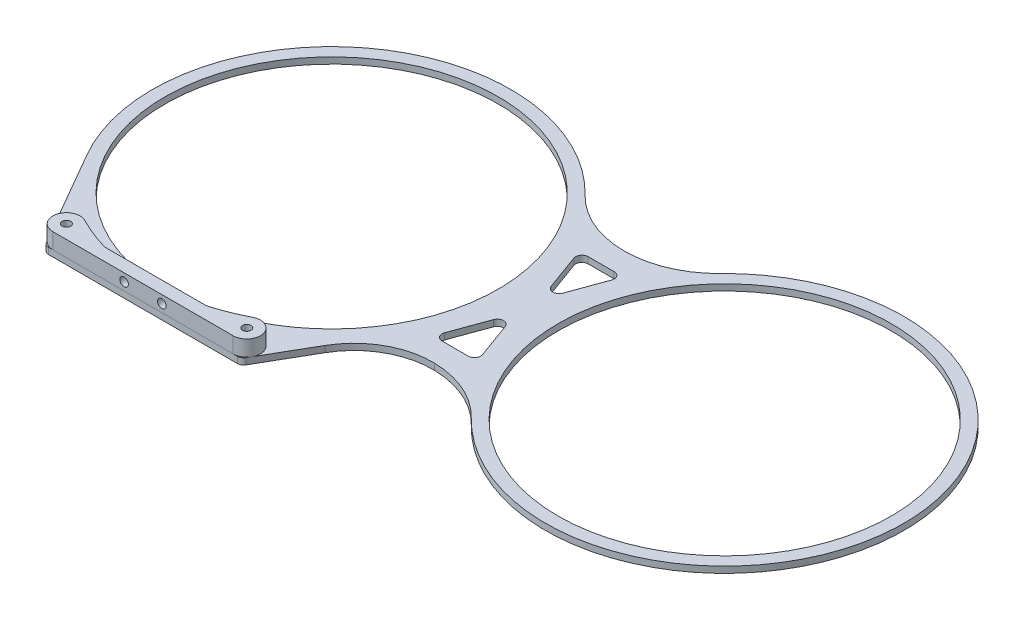
SolidWorks part; units mm, degrees
ref_plane "前视基准面" through (0, 0, 0) normal (0, 0, 1) x (1, 0, 0)
ref_plane "上视基准面" through (0, 0, 0) normal (0, 1, 0) x (1, 0, 0)
ref_plane "右视基准面" through (0, 0, 0) normal (1, 0, 0) x (0, 0, -1)
sketch "草图1" plane through (0, 0, 0) normal (0, 1, 0) x (1, 0, 0)
  line L0 (0, 0) -> (125, 0) construction
  line L1 (0, 0) -> (0, -113.6552) construction
  line L2 (-10.1, -70.4438) -> (-10.1, -59.1438) construction
  line L3 (10.1, -89.1438) -> (10.1, -59.1438) construction
  line L8 (62.5, 30.5207) -> (62.5, -30.5207) construction
  line L9 (55.5, 23.2323) -> (62.5, 4)
  line L10 (55.5, 23.2323) -> (69.5, 23.2323)
  line L11 (69.5, 23.2323) -> (62.5, 4)
  line L12 (55.5, -23.2323) -> (69.5, -23.2323)
  line L13 (55.5, -23.2323) -> (62.5, -4)
  line L14 (69.5, -23.2323) -> (62.5, -4)
  line L15 (-31.1769, -60) -> (31.1769, -60)
  line L18 (10.1, -70.4438) -> (10.1, -60) construction
  line L19 (10.1, -60) -> (31.1769, -60) construction
  line L20 (-31.1769, -60) -> (-49.3634, -28.5)
  line L23 (31.1769, -60) -> (44.9051, -36.2221)
  line L24 (-31.1769, -60) -> (-28.6769, -55.6699) construction
  circle A0 centre (0, 0) radius 53
  arc A1 (40.9483, 39.6515) -> (-49.3634, -28.5) centre (0, 0) ccw
  circle A2 centre (125, 0) radius 53
  arc A3 (84.0517, -39.6515) -> (84.0517, 39.6515) centre (125, 0) ccw
  arc A4 (40.9483, 39.6515) -> (84.0517, 39.6515) centre (62.5, 60.5207) ccw
  arc A5 (44.9051, -36.2221) -> (84.0517, -39.6515) centre (62.5, -60.5207) cw
  circle A7 centre (-28.6769, -55.6699) radius 1.35
  circle A8 centre (28.6769, -55.6699) radius 1.35
  point P26 (62.5, 23.2323)
  dimension "D1" = 106
  dimension "D2" = 114
  dimension "D3" = 125
  dimension "D4" = 30
  dimension "D12" = 5
  dimension "D13" = 2.7
  dimension "D5" = 20.2
  dimension "D6" = 60
  dimension "D7" = 120
  dimension "D8" = 7
  dimension "D9" = 70
  dimension "D10" = 4
  dimension "D11" = 120
extrude "凸台-拉伸1" add sketch "草图1" along normal blind 2
fillet "圆角1" radius 2 8 edges at (62.5, 1, -4) (55.5, 1, -23.2323) (69.5, 1, -23.2323) (69.5, 1, 23.2323) (55.5, 1, 23.2323) (62.5, 1, 4) (31.1769, 1, 60) (-31.1769, 1, 60)
fillet "圆角2" radius 25 1 edges at (44.9051, 1, 36.2221)
sketch "草图12" plane through (0, 2, 0) normal (0, 1, 0) x (1, 0, 0)
  line L0 (0, -60) -> (0, -53) construction
  line L1 (-30.0222, -60) -> (30.0222, -60) construction
  line L2 (-28.6769, -60) -> (28.6769, -60)
  line L3 (-16.1842, -56) -> (16.1842, -56)
  arc A0 (-26.694, -51.8205) -> (-28.6769, -60) centre (-28.6769, -55.6699) ccw
  circle A1 centre (0, 0) radius 53 construction
  arc A2 (26.694, -51.8205) -> (28.6769, -60) centre (28.6769, -55.6699) cw
  arc A3 (-26.694, -51.8205) -> (-16.1842, -56) centre (0, 0) ccw
  arc A4 (16.1842, -56) -> (26.694, -51.8205) centre (0, 0) ccw
  circle A5 centre (-28.6769, -55.6699) radius 1.35
  circle A6 centre (28.6769, -55.6699) radius 1.35
  dimension "D1" = 4
  dimension "D2" = 2.7
extrude "凸台-拉伸6" add sketch "草图12" along normal blind 5 separate body
sketch "草图13" plane through (0, 0, 60) normal (0, 0, 1) x (1, 0, 0)
  line L0 (0, 2) -> (0, 7) construction
  line L1 (-28.6769, 2) -> (28.6769, 2) construction
  line L2 (-28.6769, 7) -> (28.6769, 7) construction
  line L3 (0, 4.5) -> (-6, 4.5) construction
  circle A0 centre (-6, 4.5) radius 1.35
  circle A1 centre (6, 4.5) radius 1.35
  dimension "D1" = 2.7
  dimension "D2" = 12
extrude "切除-拉伸1" cut sketch "草图13" against normal through all
move or copy body "实体-移动/复制1" [suppressed] bodies to move or copy 106 125
